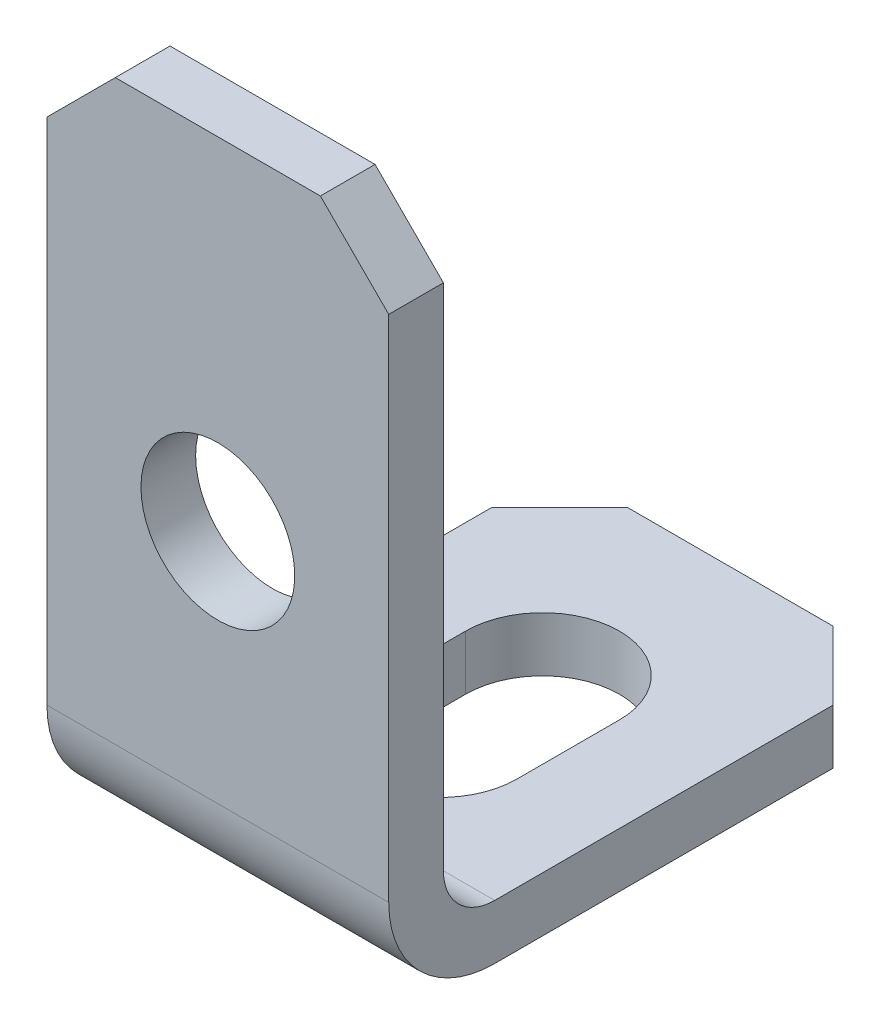
SolidWorks part; units mm, degrees
ref_plane "Front Plane" through (0, 0, 0) normal (0, 0, 1) x (1, 0, 0)
ref_plane "Top Plane" through (0, 0, 0) normal (0, 1, 0) x (1, 0, 0)
ref_plane "Right Plane" through (0, 0, 0) normal (1, 0, 0) x (0, 0, -1)
ref_plane "Plane1" through (10, 0, 0) normal (1, 0, 0) x (0, 0, -1)
sketch "Sketch1" plane through (10, 0, 0) normal (1, 0, 0) x (0, 0, -1)
  line L0 (0, 20) -> (0, 0)
  line L1 (0, 0) -> (15, 0)
  line L2 (15, 0) -> (15, 20)
  line L3 (15, 20) -> (0, 20)
extrude "Boss-Extrude1" add sketch "Sketch1" against normal blind 10
sketch "Sketch2" plane through (0, 0, 0) normal (-1, 0, 0) x (0, 0, 1)
  line L0 (-15, 1.6) -> (-1.6, 1.6)
  line L1 (-1.6, 1.6) -> (-1.6, 20)
  line L2 (-1.6, 20) -> (-15, 20)
  line L3 (-15, 20) -> (-15, 1.6)
extrude "Cut-Extrude1" cut sketch "Sketch2" against normal through all
sketch "Sketch3" plane through (0, 0, 0) normal (0, -1, 0) x (1, 0, 0)
  line L0 (7.25, -9.5) -> (7.25, -6.5)
  line L1 (2.75, -6.5) -> (2.75, -9.5)
  arc A0 (2.75, -9.5) -> (7.25, -9.5) centre (5, -9.5) ccw
  arc A1 (7.25, -6.5) -> (2.75, -6.5) centre (5, -6.5) ccw
extrude "Cut-Extrude2" cut sketch "Sketch3" against normal through all
hole_wizard "Ø4.5 (4.5) Diameter Hole1" positions "Sketch5" profile "Sketch4" hole size "Ø4.5" standard "ANSI Metric"
sketch "Sketch5" plane through (0, 0, -1.6) normal (0, 0, -1) x (-1, 0, 0)
  point P0 (-5, 10)
sketch "Sketch4" plane through (5, 10, -1.6) normal (1, 0, 0) x (0, 1, 0)
  line L0 (0, 0) -> (0, 1.6)
  line L1 (0, 1.6) -> (2.25, 1.6)
  line L2 (2.25, 1.6) -> (2.25, 0)
  line L5 (2.25, 0) -> (0, 0)
  line L11 (0, -6.35) -> (0, 107.95) construction
  dimension "Thru Hole Dia." = 4.5
  dimension "Thru Hole Depth" = 1.6
chamfer "Chamfer1" distance 2 angle 45 4 edges at (0, 20, -0.8) (0, 0.8, -15) (10, 0.8, -15) (10, 20, -0.8)
fillet "Fillet1" radius 1.5 1 edges at (5, 1.6, -1.6)
fillet "Fillet2" radius 3.1 1 edges at (5, 0, 0)
